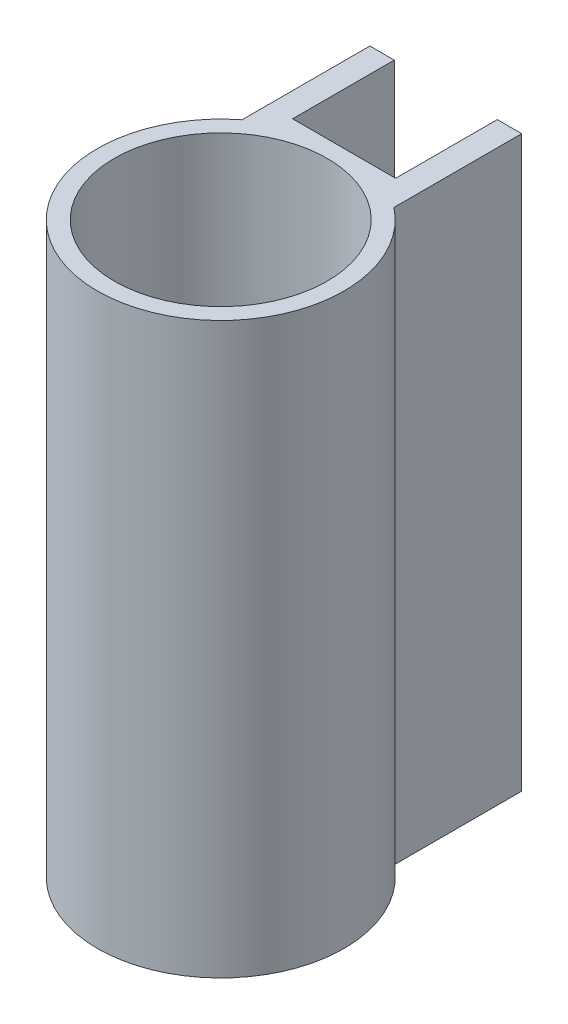
SolidWorks part; units mm, degrees
ref_plane "Front Plane" through (0, 0, 0) normal (0, 0, 1) x (1, 0, 0)
ref_plane "Top Plane" through (0, 0, 0) normal (0, 1, 0) x (1, 0, 0)
ref_plane "Right Plane" through (0, 0, 0) normal (1, 0, 0) x (0, 0, -1)
sketch "Sketch1" plane through (0, 0, 0) normal (0, 1, 0) x (1, 0, 0)
  circle A0 centre (0, 0) radius 23.114
  circle A1 centre (0, 0) radius 9.652
  dimension "D1" = 19.304
  dimension "D2" = 46.228
extrude "Boss-Extrude1" add sketch "Sketch1" along normal blind 5.08
sketch "Sketch2" plane through (0, 5.08, 0) normal (0, 1, 0) x (1, 0, 0)
  line L0 (-14.224, 18.2191) -> (-14.224, 42.164)
  line L1 (-14.224, 42.164) -> (-9.652, 42.164)
  line L2 (-9.652, 42.164) -> (-9.652, 23.114)
  line L3 (-9.652, 23.114) -> (9.652, 23.114)
  line L4 (9.652, 23.114) -> (9.652, 42.164)
  line L5 (9.652, 42.164) -> (14.224, 42.164)
  line L6 (14.224, 42.164) -> (14.224, 18.2191)
  line L7 (0, 23.114) -> (0, 0) construction
  arc A0 (-14.224, 18.2191) -> (14.224, 18.2191) centre (0, 0) ccw
  circle A1 centre (0, 0) radius 19.939
  circle A2 centre (0, 0) radius 23.114 construction
  point P8 (0, 19.939)
  dimension "D1" = 3.175
  dimension "D2" = 19.304
  dimension "D3" = 4.572
  dimension "D4" = 3.175
  dimension "D5" = 19.05
extrude "Boss-Extrude2" add sketch "Sketch2" along normal blind 101.6 and the other way up to surface other way up to face at (0, 0, 23.114)
equation "\"Body Size\"= 1.56in"
equation "\"clearance\"= 0.01in"
equation "\"Wall thickness\"= 0.125in"
